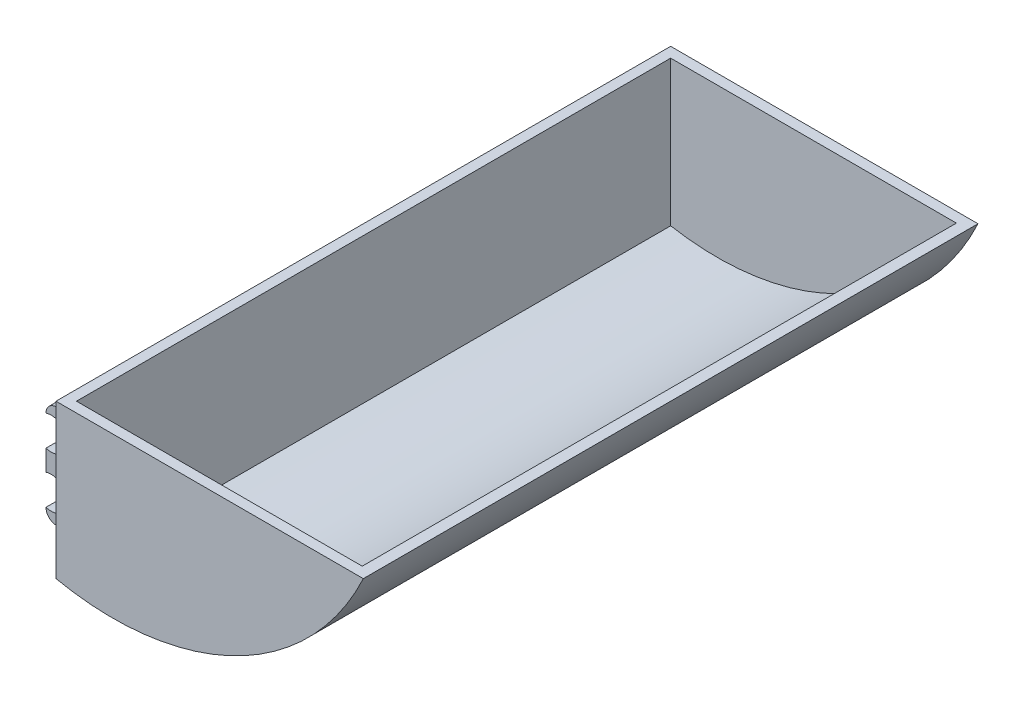
SolidWorks part; units mm, degrees
ref_plane "Front Plane" through (0, 0, 0) normal (0, 0, 1) x (1, 0, 0)
ref_plane "Top Plane" through (0, 0, 0) normal (0, 1, 0) x (1, 0, 0)
ref_plane "Right Plane" through (0, 0, 0) normal (1, 0, 0) x (0, 0, -1)
sketch "Sketch1" plane through (0, 0, 0) normal (0, 0, 1) x (1, 0, 0)
  line L0 (0, 0) -> (0, 38.1)
  line L1 (0, 38.1) -> (76.2, 38.1)
  arc A0 (76.2, 38.1) -> (0, 0) centre (14.0638, 67.1225) cw
  dimension "D3" = 68.58
  dimension "D1" = 76.2
  dimension "D2" = 38.1
extrude "Boss-Extrude1" add sketch "Sketch1" along normal blind 152.4
shell "Shell1" thickness 2.54
sketch "Sketch2" plane through (0, 0, 0) normal (1, 0, 0) x (0, 0, -1)
  line L0 (-76.2, 38.1) -> (-76.2, 0) construction
  line L1 (-152.4, 38.1) -> (0, 38.1) construction
  line L2 (-152.4, 0) -> (0, 0) construction
  line L3 (0, 19.05) -> (-152.4, 19.05) construction
  line L4 (0, 38.1) -> (0, 0) construction
  line L5 (-152.4, 38.1) -> (-152.4, 0) construction
  line L7 (-5.1435, 31.75) -> (-13.081, 31.75)
  line L8 (-5.1435, 31.75) -> (-5.1435, 6.35)
  line L9 (-5.1435, 6.35) -> (-13.081, 6.35)
  line L10 (-13.081, 31.75) -> (-13.081, 6.35)
  dimension "D1" = 7.9375
  dimension "D2" = 63.119
  dimension "D3" = 25.4
extrude "Boss-Extrude2" add sketch "Sketch2" against normal blind 7.62
sketch "Sketch3" plane through (0, 0, 5.1435) normal (0, 0, -1) x (-1, 0, 0)
  line L0 (7.62, 19.05) -> (0, 19.05) construction
  line L1 (7.62, 6.35) -> (7.62, 31.75) construction
  line L2 (0, 38.1) -> (0, 0) construction
  circle A0 centre (6.35, 25.4) radius 3.9624
  circle A1 centre (6.35, 12.7) radius 3.9624
  dimension "D2" = 7.9248
  dimension "D1" = 12.7
  dimension "D3" = 1.27
extrude "Cut-Extrude1" cut sketch "Sketch3" against normal blind 12.7
fillet "Fillet1" radius 2.54 4 edges at (-7.62, 6.35, 9.1123) (0, 6.35, 9.1123) (-7.62, 31.75, 9.1123) (0, 31.75, 9.1123)
ref_plane "Plane1" through (0, 0, 76.2) normal (0, 0, -1) x (-1, 0, 0)
mirror "Mirror1" about plane through (0, 0, 76.2) normal (0, 0, -1) of "Fillet1", "Cut-Extrude1", "Boss-Extrude2"
ref_plane "Plane2" through (0, 0, 143.2877) normal (0, 0, 1) x (1, 0, 0)
